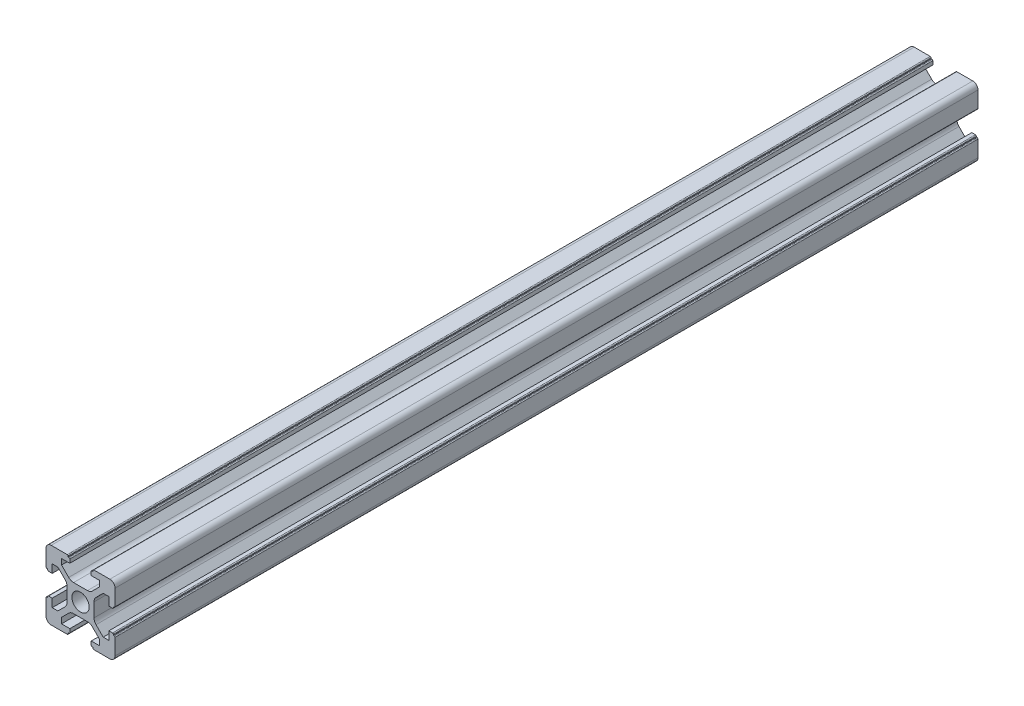
SolidWorks part; units mm, degrees
ref_plane "Front Plane" through (0, 0, 0) normal (0, 0, 1) x (1, 0, 0)
ref_plane "Top Plane" through (0, 0, 0) normal (0, 1, 0) x (1, 0, 0)
ref_plane "Right Plane" through (0, 0, 0) normal (1, 0, 0) x (0, 0, -1)
sketch "Sketch1" plane through (0, 0, 0) normal (0, 0, 1) x (1, 0, 0)
  line L0 (0, 0) -> (-10, 10) construction
  line L5 (0, 0) -> (10, 10) construction
  line L6 (22.7721, 0) -> (-22.7721, 0) construction
  line L7 (-8.5, 10) -> (-3.85, 10)
  line L8 (8.5, 10) -> (3.85, 10)
  line L9 (-3.6, 9.75) -> (-3.6, 9.5)
  line L10 (-3.6, 9.5) -> (-3.35, 9.5)
  line L11 (3.6, 9.75) -> (3.6, 9.5)
  line L12 (3.6, 9.5) -> (3.35, 9.5)
  line L13 (-3.1, 9.25) -> (-3.1, 8.2)
  line L14 (3.1, 9.25) -> (3.1, 8.2)
  line L15 (-3.1, 8.2) -> (-5.5, 8.2)
  line L16 (3.1, 8.2) -> (5.5, 8.2)
  line L17 (-3.4251, 4.4858) -> (-5.5, 6.5607)
  line L18 (-2.0109, 3.9) -> (2.0109, 3.9)
  line L19 (-5.5, 6.5607) -> (-5.5, 8.2)
  line L20 (5.5, 6.5607) -> (3.4251, 4.4858)
  line L21 (5.5, 6.5607) -> (5.5, 8.2)
  line L22 (10, 8.5) -> (10, 3.85)
  line L23 (10, -8.5) -> (10, -3.85)
  line L24 (9.75, 3.6) -> (9.5, 3.6)
  line L25 (9.5, 3.6) -> (9.5, 3.35)
  line L26 (9.75, -3.6) -> (9.5, -3.6)
  line L27 (9.5, -3.6) -> (9.5, -3.35)
  line L28 (9.25, 3.1) -> (8.2, 3.1)
  line L29 (9.25, -3.1) -> (8.2, -3.1)
  line L30 (8.2, 3.1) -> (8.2, 5.5)
  line L31 (8.2, -3.1) -> (8.2, -5.5)
  line L32 (4.4858, 3.4251) -> (6.5607, 5.5)
  line L33 (3.9, 2.0109) -> (3.9, -2.0109)
  line L34 (6.5607, 5.5) -> (8.2, 5.5)
  line L35 (6.5607, -5.5) -> (4.4858, -3.4251)
  line L36 (6.5607, -5.5) -> (8.2, -5.5)
  line L37 (8.5, -10) -> (3.85, -10)
  line L38 (-8.5, -10) -> (-3.85, -10)
  line L39 (3.6, -9.75) -> (3.6, -9.5)
  line L40 (3.6, -9.5) -> (3.35, -9.5)
  line L41 (-3.6, -9.75) -> (-3.6, -9.5)
  line L42 (-3.6, -9.5) -> (-3.35, -9.5)
  line L43 (3.1, -9.25) -> (3.1, -8.2)
  line L44 (-3.1, -9.25) -> (-3.1, -8.2)
  line L45 (3.1, -8.2) -> (5.5, -8.2)
  line L46 (-3.1, -8.2) -> (-5.5, -8.2)
  line L47 (3.4251, -4.4858) -> (5.5, -6.5607)
  line L48 (2.0109, -3.9) -> (-2.0109, -3.9)
  line L49 (5.5, -6.5607) -> (5.5, -8.2)
  line L50 (-5.5, -6.5607) -> (-3.4251, -4.4858)
  line L51 (-5.5, -6.5607) -> (-5.5, -8.2)
  line L52 (-10, -8.5) -> (-10, -3.85)
  line L53 (-10, 8.5) -> (-10, 3.85)
  line L54 (-9.75, -3.6) -> (-9.5, -3.6)
  line L55 (-9.5, -3.6) -> (-9.5, -3.35)
  line L56 (-9.75, 3.6) -> (-9.5, 3.6)
  line L57 (-9.5, 3.6) -> (-9.5, 3.35)
  line L58 (-9.25, -3.1) -> (-8.2, -3.1)
  line L59 (-9.25, 3.1) -> (-8.2, 3.1)
  line L60 (-8.2, -3.1) -> (-8.2, -5.5)
  line L61 (-8.2, 3.1) -> (-8.2, 5.5)
  line L62 (-4.4858, -3.4251) -> (-6.5607, -5.5)
  line L63 (-3.9, -2.0109) -> (-3.9, 2.0109)
  line L64 (-6.5607, -5.5) -> (-8.2, -5.5)
  line L65 (-6.5607, 5.5) -> (-4.4858, 3.4251)
  line L66 (-6.5607, 5.5) -> (-8.2, 5.5)
  circle A5 centre (0, 0) radius 2.5
  arc A6 (-8.5, -10) -> (-10, -8.5) centre (-8.5, -8.5) cw
  arc A7 (10, -8.5) -> (8.5, -10) centre (8.5, -8.5) cw
  arc A8 (8.5, 10) -> (10, 8.5) centre (8.5, 8.5) cw
  arc A9 (-8.5, 10) -> (-10, 8.5) centre (-8.5, 8.5) ccw
  arc A10 (-4.4858, -3.4251) -> (-3.9, -2.0109) centre (-5.9, -2.0109) ccw
  arc A11 (-2.0109, -3.9) -> (-3.4251, -4.4858) centre (-2.0109, -5.9) ccw
  arc A12 (3.4251, -4.4858) -> (2.0109, -3.9) centre (2.0109, -5.9) ccw
  arc A13 (3.9, -2.0109) -> (4.4858, -3.4251) centre (5.9, -2.0109) ccw
  arc A14 (4.4858, 3.4251) -> (3.9, 2.0109) centre (5.9, 2.0109) ccw
  arc A15 (3.4251, 4.4858) -> (2.0109, 3.9) centre (2.0109, 5.9) cw
  arc A16 (-3.4251, 4.4858) -> (-2.0109, 3.9) centre (-2.0109, 5.9) ccw
  arc A17 (-3.9, 2.0109) -> (-4.4858, 3.4251) centre (-5.9, 2.0109) ccw
  arc A18 (10, 3.85) -> (9.75, 3.6) centre (9.75, 3.85) cw
  arc A19 (9.5, 3.35) -> (9.25, 3.1) centre (9.25, 3.35) cw
  arc A20 (10, -3.85) -> (9.75, -3.6) centre (9.75, -3.85) ccw
  arc A21 (9.5, -3.35) -> (9.25, -3.1) centre (9.25, -3.35) ccw
  arc A22 (3.85, -10) -> (3.6, -9.75) centre (3.85, -9.75) cw
  arc A23 (3.1, -9.25) -> (3.35, -9.5) centre (3.35, -9.25) ccw
  arc A24 (-3.1, -9.25) -> (-3.35, -9.5) centre (-3.35, -9.25) cw
  arc A25 (-3.85, -10) -> (-3.6, -9.75) centre (-3.85, -9.75) ccw
  arc A26 (-10, -3.85) -> (-9.75, -3.6) centre (-9.75, -3.85) cw
  arc A27 (-9.25, -3.1) -> (-9.5, -3.35) centre (-9.25, -3.35) ccw
  arc A28 (-9.5, 3.35) -> (-9.25, 3.1) centre (-9.25, 3.35) ccw
  arc A29 (-10, 3.85) -> (-9.75, 3.6) centre (-9.75, 3.85) ccw
  arc A30 (-3.1, 9.25) -> (-3.35, 9.5) centre (-3.35, 9.25) ccw
  arc A31 (-3.85, 10) -> (-3.6, 9.75) centre (-3.85, 9.75) cw
  arc A32 (3.35, 9.5) -> (3.1, 9.25) centre (3.35, 9.25) ccw
  arc A33 (3.85, 10) -> (3.6, 9.75) centre (3.85, 9.75) ccw
  point P6 (-3.1, 9.5)
  point P7 (0, 0)
  point P28 (9.5, 3.1)
  point P46 (3.1, -9.5)
  point P63 (-9.5, -3.1)
  point P77 (0, 0)
  point P123 (-3.1, 9.5)
  point P126 (-3.6, 10)
  point P129 (3.1, 9.5)
  point P132 (3.6, 10)
  dimension "D1" = 45
  dimension "D4" = 7.2
  dimension "D2" = 5
  dimension "D13" = 1.5
  dimension "D14" = 2
  dimension "D15" = 0.25
  dimension "D3" = 20
  dimension "D5" = 0.5
  dimension "D6" = 6.2
  dimension "D7" = 1.8
  dimension "D8" = 11
  dimension "D9" = 0.75
  dimension "D10" = 6.1
  dimension "D11" = 0.75
  dimension "D12" = 4
extrude "Boss-Extrude1" add sketch "Sketch1" along normal blind 250
